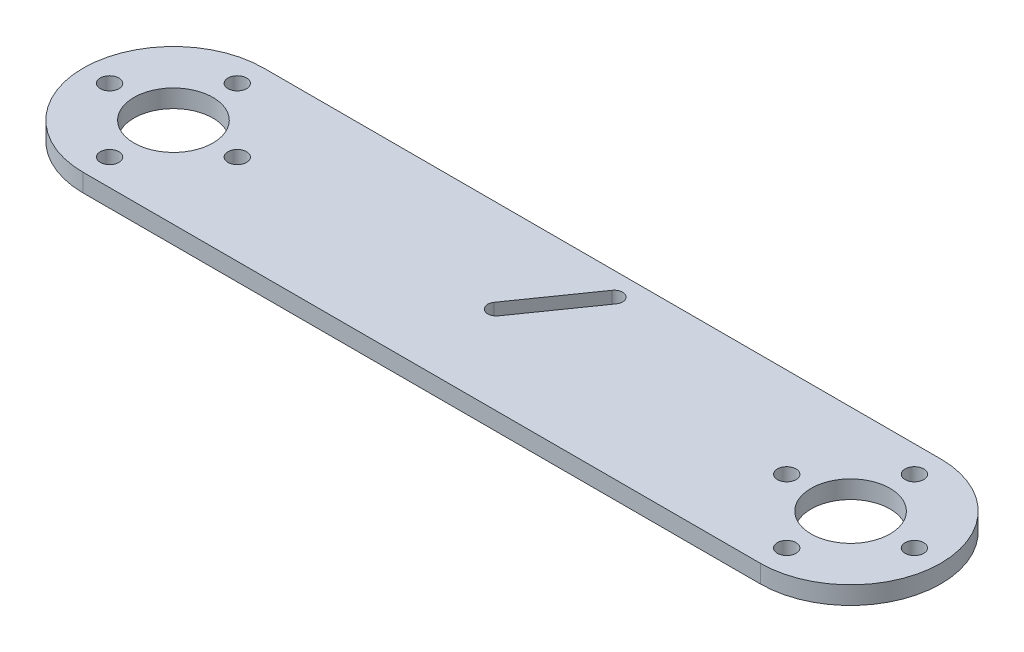
SolidWorks part; units mm, degrees
ref_plane "Front" through (0, 0, 0) normal (0, 0, 1) x (1, 0, 0)
ref_plane "Top" through (0, 0, 0) normal (0, 1, 0) x (1, 0, 0)
ref_plane "Right" through (0, 0, 0) normal (1, 0, 0) x (0, 0, -1)
sketch "Sketch1" plane through (0, 0, 0) normal (0, 1, 0) x (1, 0, 0)
  line L0 (69.0686, 32) -> (52.6733, 8.5851)
  line L1 (0, 0) -> (120, 0)
  line L2 (0, 0) -> (0, 32)
  line L3 (0, 32) -> (120, 32)
  line L4 (120, 0) -> (120, 32)
  line L5 (57.597, 15.617) -> (66.2007, 27.9042) construction
  line L6 (56.3683, 16.4773) -> (64.972, 28.7646)
  line L7 (58.8258, 14.7566) -> (67.4294, 27.0439)
  arc A0 (0, 32) -> (0, 0) centre (0, 16) ccw
  arc A1 (120, 32) -> (120, 0) centre (120, 16) cw
  circle A2 centre (0, 16) radius 7
  circle A3 centre (120, 16) radius 7
  arc A4 (56.3683, 16.4773) -> (58.8258, 14.7566) centre (57.597, 15.617) ccw
  arc A5 (67.4294, 27.0439) -> (64.972, 28.7646) centre (66.2007, 27.9042) ccw
  point P13 (61.8989, 21.7606)
  dimension "D3" = 15
  dimension "D4" = 5
  dimension "D5" = 1.5
  dimension "D1" = 32
  dimension "D2" = 120
extrude "Boss-Extrude1" add sketch "Sketch1" along normal blind 3.175 contours A3 L4 L3 L2 A2 L1 | A2 L2 A0 | A3 L4 A1
sketch "Sketch2" plane through (0, 3.175, 0) normal (0, 1, 0) x (1, 0, 0)
  line L0 (0, 16) -> (11.3137, 16)
  line L1 (60, 32) -> (60, 0)
  line L2 (0, 32) -> (120, 32) construction
  line L3 (0, 0) -> (120, 0) construction
  circle A0 centre (0, 16) radius 11.3137
  circle A1 centre (0, 27.3137) radius 1.65
  circle A2 centre (0, 4.6863) radius 1.65
  circle A3 centre (11.3137, 16) radius 1.65
  circle A4 centre (-11.3137, 16) radius 1.65
  circle A5 centre (120, 27.3137) radius 1.65
  circle A6 centre (131.3137, 16) radius 1.65
  circle A7 centre (120, 4.6863) radius 1.65
  circle A8 centre (108.6863, 16) radius 1.65
  dimension "D1" = 11.3137
extrude "Cut-Extrude1" cut sketch "Sketch2" against normal blind 10 contours A5 | A8 | A7 | A6 | A4 | A1 | A3 | A2
